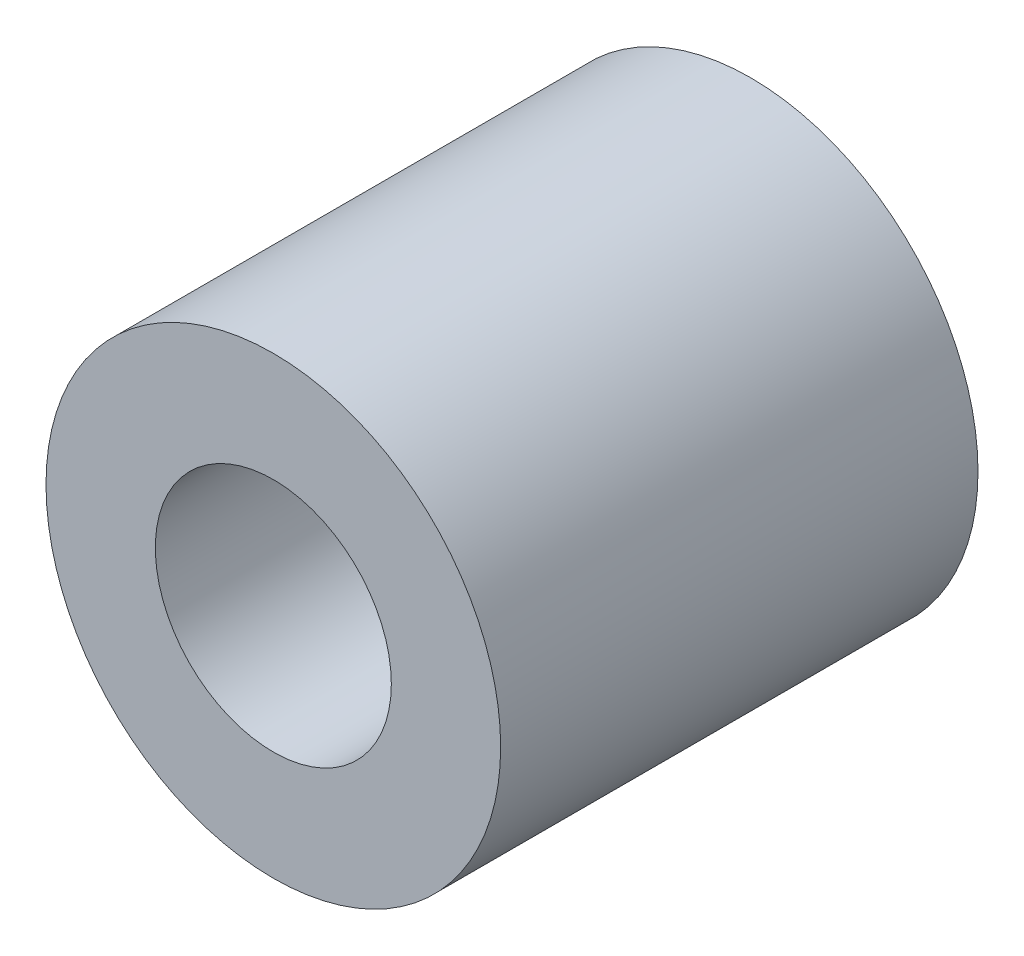
SolidWorks part; units mm, degrees
ref_plane "정면" through (0, 0, 0) normal (0, 0, 1) x (1, 0, 0)
ref_plane "윗면" through (0, 0, 0) normal (0, 1, 0) x (1, 0, 0)
ref_plane "우측면" through (0, 0, 0) normal (1, 0, 0) x (0, 0, -1)
sketch "스케치1" plane through (0, 0, 0) normal (0, 0, 1) x (1, 0, 0)
  circle A0 centre (0, 0) radius 47.624
  circle A1 centre (0, 0) radius 24.7235
extrude "보스-돌출1" add sketch "스케치1" along normal blind 100
